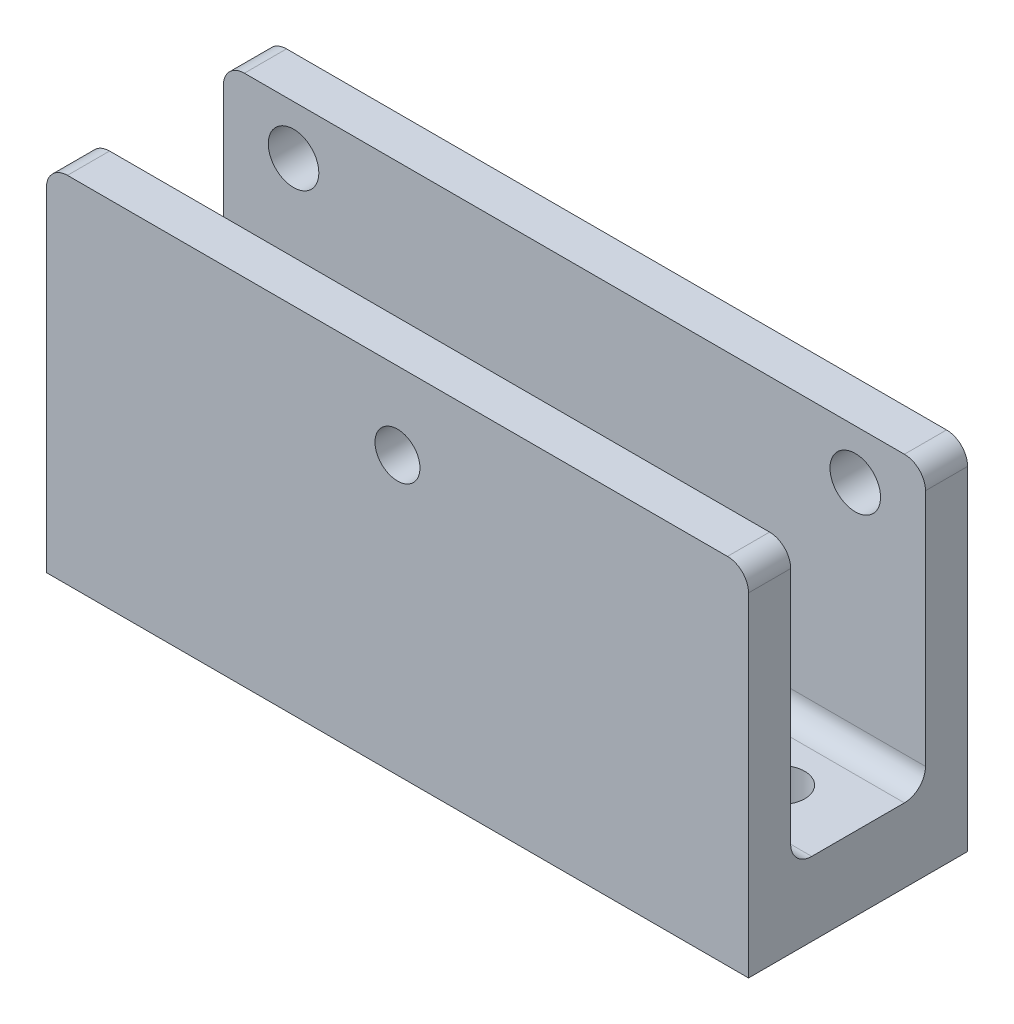
SolidWorks part; units mm, degrees
ref_plane "Front Plane" through (0, 0, 0) normal (0, 0, 1) x (1, 0, 0)
ref_plane "Top Plane" through (0, 0, 0) normal (0, 1, 0) x (1, 0, 0)
ref_plane "Right Plane" through (0, 0, 0) normal (1, 0, 0) x (0, 0, -1)
sketch "Sketch1" plane through (0, 0, 0) normal (0, 1, 0) x (1, 0, 0)
  line L1 (-25, 4.8) -> (25, 4.8)
  line L2 (-25, 4.8) -> (-25, -4.8)
  line L3 (-25, -4.8) -> (25, -4.8)
  line L4 (25, 4.8) -> (25, -4.8)
  line L5 (-25, 4.8) -> (25, -4.8) construction
  line L6 (-25, -4.8) -> (25, 4.8) construction
  point P0 (0, 0)
  point P8 (0, 0)
  dimension "D1" = 9.6
  dimension "D2" = 50
extrude "Boss-Extrude1" add sketch "Sketch1" along normal blind 5.25
sketch "Sketch2" plane through (0, 0, 0) normal (0, -1, 0) x (1, 0, 0)
  line L0 (-5.5, 0) -> (5.5, 0) construction
  circle A0 centre (-19.5, 0) radius 2.5
  circle A1 centre (-5.5, 0) radius 2.5
  circle A2 centre (5.5, 0) radius 2.5
  circle A3 centre (19.5, 0) radius 2.5
  point P8 (0, 0)
  dimension "D1" = 5
  dimension "D2" = 14
  dimension "D3" = 14
  dimension "D4" = 11
extrude "Cut-Extrude1" cut sketch "Sketch2" against normal blind 2.1
hole_wizard "M3 Clearance Hole1" positions "Sketch3" profile "Sketch4" hole size "M3" standard "ANSI Metric"
sketch "Sketch3" plane through (0, 5.25, 0) normal (0, 1, 0) x (1, 0, 0)
  circle A0 centre (19.5, 0) radius 2.5 construction
  circle A1 centre (5.5, 0) radius 2.5 construction
  circle A2 centre (-5.5, 0) radius 2.5 construction
  circle A3 centre (-19.5, 0) radius 2.5 construction
  point P0 (-19.5, 0)
  point P2 (-5.5, 0)
  point P4 (5.5, 0)
  point P6 (19.5, 0)
  point P9 (0, 0)
  point P12 (0, 0)
  point P15 (0, 0)
  point P18 (0, 0)
sketch "Sketch4" plane through (-19.5, 5.25, 0) normal (1, 0, 0) x (0, 0, 1)
  line L0 (0, 0) -> (0, 9)
  line L1 (0, 9) -> (1.7, 7.9785)
  line L2 (1.7, 7.9785) -> (1.7, 0)
  line L5 (1.7, 0) -> (0, 0)
  line L10 (0, 9) -> (-1.7, 7.9785) construction
  line L11 (0, -6.35) -> (0, 107.95) construction
  dimension "Hole Dia." = 3.4
  dimension "Hole Depth" = 9
  dimension "Drill Angle" = 118
sketch "Sketch5" plane through (0, 0, 4.8) normal (0, 0, 1) x (1, 0, 0)
  line L0 (25, 5.25) -> (25, 0) construction
  line L1 (-25, 0) -> (25, 0)
  line L2 (-25, 0) -> (-25, 25.25)
  line L3 (-25, 25.25) -> (25, 25.25)
  line L4 (25, 0) -> (25, 25.25)
  line L5 (-25, 0) -> (25, 25.25) construction
  line L6 (-25, 25.25) -> (25, 0) construction
  line L7 (-25, 5.25) -> (25, 5.25) construction
  point P4 (0, 12.625)
  dimension "D1" = 20
extrude "Boss-Extrude2" add sketch "Sketch5" along normal blind 3
mirror "Mirror1" about plane through (0, 0, 0) normal (0, 0, 1) of "Boss-Extrude2"
fillet "Fillet1" radius 1.5 2 edges at (0, 5.25, 4.8) (0, 5.25, -4.8)
hole_wizard "M3 Clearance Hole4" positions "Sketch6" profile "Sketch7" hole size "M3" standard "ANSI Metric"
sketch "Sketch6" plane through (0, 0, 7.8) normal (0, 0, 1) x (1, 0, 0)
  line L0 (25, 25.25) -> (-25, 25.25) construction
  point P0 (0, 19.75)
  point P10 (0, 0)
  dimension "D1" = 5.5
sketch "Sketch7" plane through (0, 19.75, 7.8) normal (1, 0, 0) x (0, -1, 0)
  line L0 (0, 0) -> (0, 4)
  line L1 (0, 4) -> (1.6, 3.0386)
  line L2 (1.6, 3.0386) -> (1.6, 0)
  line L5 (1.6, 0) -> (0, 0)
  line L10 (0, 4) -> (-1.6, 3.0386) construction
  line L11 (0, -6.35) -> (0, 107.95) construction
  dimension "Hole Dia." = 3.2
  dimension "Hole Depth" = 4
  dimension "Drill Angle" = 118
hole_wizard "M3 Clearance Hole5" positions "Sketch9" profile "Sketch10" hole size "M3" standard "ANSI Metric"
sketch "Sketch9" plane through (0, 0, -7.8) normal (0, 0, -1) x (-1, 0, 0)
  line L0 (-20, 21.75) -> (20, 21.75)
  line L2 (25, 25.25) -> (25, 0) construction
  line L8 (-12.75, 11.75) -> (12.75, 11.75) construction
  line L9 (-25, 25.25) -> (25, 25.25) construction
  point P0 (-20, 21.75)
  point P4 (20, 21.75)
  point P6 (12.75, 11.75)
  point P8 (-12.75, 11.75)
  point P76 (0, 11.75)
  point P77 (0, 21.75)
  dimension "D1" = 5
  dimension "D2" = 40
  dimension "D3" = 10
  dimension "D4" = 25.5
  dimension "D5" = 3.5
sketch "Sketch10" plane through (20, 21.75, -7.8) normal (1, 0, 0) x (0, 1, 0)
  line L0 (0, 0) -> (0, 5)
  line L1 (0, 5) -> (1.8, 3.9185)
  line L2 (1.8, 3.9185) -> (1.8, 0)
  line L5 (1.8, 0) -> (0, 0)
  line L10 (0, 5) -> (-1.8, 3.9185) construction
  line L11 (0, -6.35) -> (0, 107.95) construction
  dimension "Hole Dia." = 3.6
  dimension "Hole Depth" = 5
  dimension "Drill Angle" = 118
fillet "Fillet2" radius 1.5 4 edges at (-25, 25.25, 6.3) (25, 25.25, -6.3) (-25, 25.25, -6.3) (25, 25.25, 6.3)
equation "\"D3@Sketch2\"=\"D2@Sketch2\""
